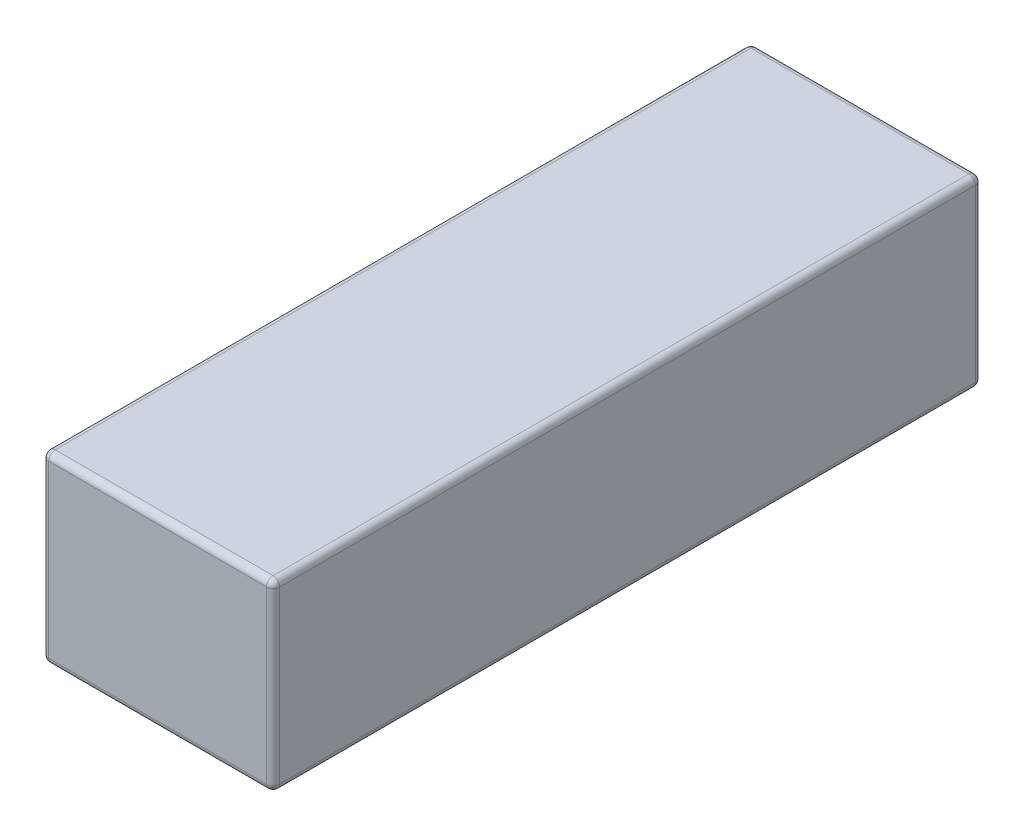
SolidWorks part; units mm, degrees
ref_plane "Front" through (0, 0, 0) normal (0, 0, 1) x (1, 0, 0)
ref_plane "Top" through (0, 0, 0) normal (0, 1, 0) x (1, 0, 0)
ref_plane "Right" through (0, 0, 0) normal (1, 0, 0) x (0, 0, -1)
sketch "Sketch1" plane through (0, 0, 0) normal (1, 0, 0) x (0, 0, -1)
  line L1 (-67.5, -17.5) -> (67.5, -17.5)
  line L2 (-67.5, -17.5) -> (-67.5, 17.5)
  line L3 (-67.5, 17.5) -> (67.5, 17.5)
  line L4 (67.5, -17.5) -> (67.5, 17.5)
  line L5 (-67.5, -17.5) -> (67.5, 17.5) construction
  line L6 (-67.5, 17.5) -> (67.5, -17.5) construction
  point P0 (0, 0)
  dimension "D1" = 135
  dimension "D2" = 35
extrude "Boss-Extrude1" add sketch "Sketch1" along normal blind 44
fillet "Fillet1" radius 1.25 12 edges at (0, -17.5, 0) (22, -17.5, -67.5) (0, 0, -67.5) (44, 0, -67.5) (44, 0, 67.5) (0, 0, 67.5) (22, -17.5, 67.5) (44, -17.5, 0) (22, 17.5, -67.5) (0, 17.5, 0) (22, 17.5, 67.5) (44, 17.5, 0)
